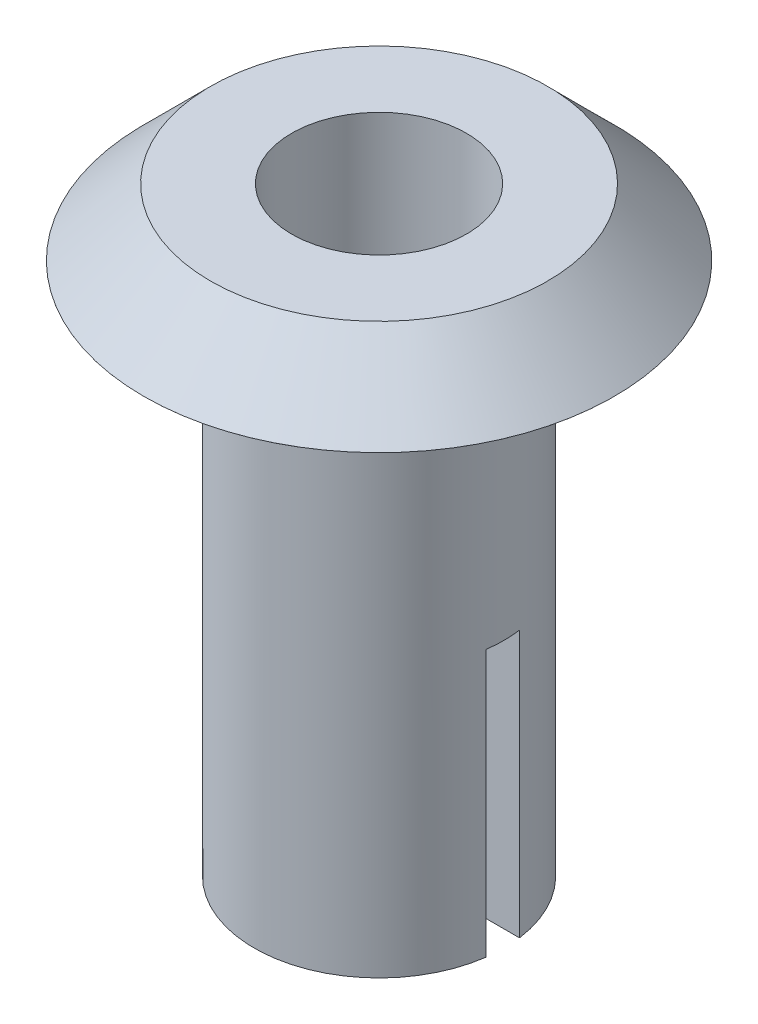
SolidWorks part; units mm, degrees
ref_plane "Alzado" through (0, 0, 0) normal (0, 0, 1) x (1, 0, 0)
ref_plane "Planta" through (0, 0, 0) normal (0, 1, 0) x (1, 0, 0)
ref_plane "Vista lateral" through (0, 0, 0) normal (1, 0, 0) x (0, 0, -1)
sketch "Croquis1" plane through (0, 0, 0) normal (0, 1, 0) x (1, 0, 0)
  circle A0 centre (0, 0) radius 1.5
extrude "Saliente-Extruir1" add sketch "Croquis1" along normal blind 7.2
sketch "Croquis2" plane through (0, 7.2, 0) normal (0, 1, 0) x (1, 0, 0)
  circle A0 centre (0, 0) radius 2.825
extrude "Saliente-Extruir2" add sketch "Croquis2" along normal blind 0.0001 and the other way blind 0.8
chamfer "Chaflán1" distance 0.8 angle 45 1 edges at (0, 7.2001, 2.825)
sketch "Croquis3" plane through (0, 7.2001, 0) normal (0, 1, 0) x (1, 0, 0)
  circle A0 centre (0, 0) radius 1.05
extrude "Cortar-Extruir1" cut sketch "Croquis3" against normal blind 5.7
fillet "Redondeo2" radius 0.8 1 edges at (0, 1.5001, 1.05)
sketch "Croquis6" plane through (0, 0, 0) normal (0, -1, 0) x (-1, 0, 0)
  line L1 (1.5, -0.2) -> (-1.5, -0.2)
  line L2 (1.5, -0.2) -> (1.5, 0.2)
  line L3 (1.5, 0.2) -> (-1.5, 0.2)
  line L4 (-1.5, -0.2) -> (-1.5, 0.2)
  line L5 (1.5, -0.2) -> (-1.5, 0.2) construction
  line L6 (1.5, 0.2) -> (-1.5, -0.2) construction
  point P0 (0, 0)
extrude "Cortar-Extruir4" cut sketch "Croquis6" against normal blind 3.2
